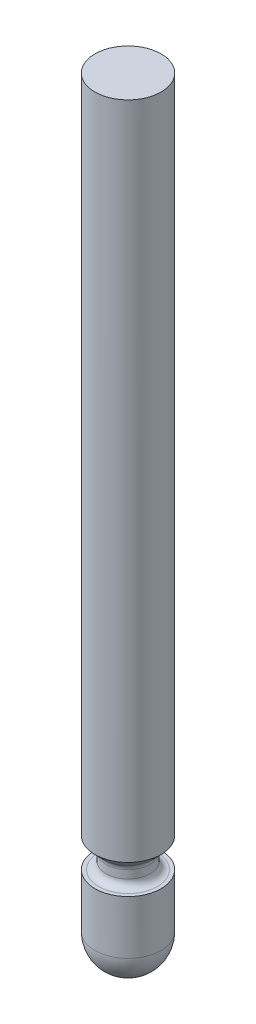
SolidWorks part; units mm, degrees
material "303 Stainless Steel"
ref_plane "Front Plane" through (0, 0, 0) normal (0, 0, 1) x (1, 0, 0)
ref_plane "Top Plane" through (0, 0, 0) normal (0, 1, 0) x (1, 0, 0)
ref_plane "Right Plane" through (0, 0, 0) normal (1, 0, 0) x (0, 0, -1)
sketch "Sketch1" plane through (0, 0, 0) normal (0, 1, 0) x (1, 0, 0)
  circle A0 centre (0, 0) radius 3.556
  dimension "D1" = 7.112
extrude "Boss-Extrude1" add sketch "Sketch1" along normal blind 83.533
sketch "Sketch3" plane through (0, 0, 0) normal (0, -1, 0) x (1, 0, 0)
  circle A0 centre (0, 0) radius 3.556
ref_plane "Plane1" through (0, 0, 0) normal (1, 0, 0) x (0, 0, -1)
sketch "Sketch2" plane through (0, 100.0148, -21.0874) normal (1, 0, 0) x (0, -1, 0)
  line L0 (100.0148, -24.6434) -> (100.0148, -17.5314) construction
  line L1 (100.0148, -24.6434) -> (100.0148, -17.5314) construction
  line L2 (100.0148, -17.5314) -> (90.6955, -17.5314) construction
  line L3 (100.0148, -17.5314) -> (16.4818, -17.5314) construction
  line L4 (90.6955, -17.5314) -> (90.6955, -24.6434) construction
  line L5 (16.4818, -24.6434) -> (100.0148, -24.6434) construction
  line L6 (90.6955, -24.6434) -> (100.0148, -24.6434) construction
  line L7 (87.5205, -8.3874) -> (87.5205, -33.7874) construction
  line L8 (90.6955, -17.5314) -> (87.5205, -17.5314)
  line L9 (100.0148, -21.0874) -> (16.4818, -21.0874) construction
  line L10 (16.4818, -17.5314) -> (16.4818, -24.6434) construction
  line L11 (90.6955, -17.5314) -> (90.6955, -17.9283)
  line L12 (89.9018, -18.7221) -> (89.04, -18.7221)
  line L13 (88.4787, -18.4896) -> (87.5205, -17.5314)
  arc A1 (89.04, -18.7221) -> (88.4787, -18.4896) centre (89.04, -17.9283) cw
  arc A2 (90.6955, -17.9283) -> (89.9018, -18.7221) centre (89.9018, -17.9283) cw
  point P22 (90.6955, -18.7221)
  dimension "D2" = 45
  dimension "D3" = 1.1906
  dimension "D4" = 0.7937
  dimension "D1" = 9.3193
revolve "Cut-Revolve2" cut sketch "Sketch2" angle 360 about L9
fillet "Fillet1" radius 3.556 1 edges at (0, 0, 3.556)
